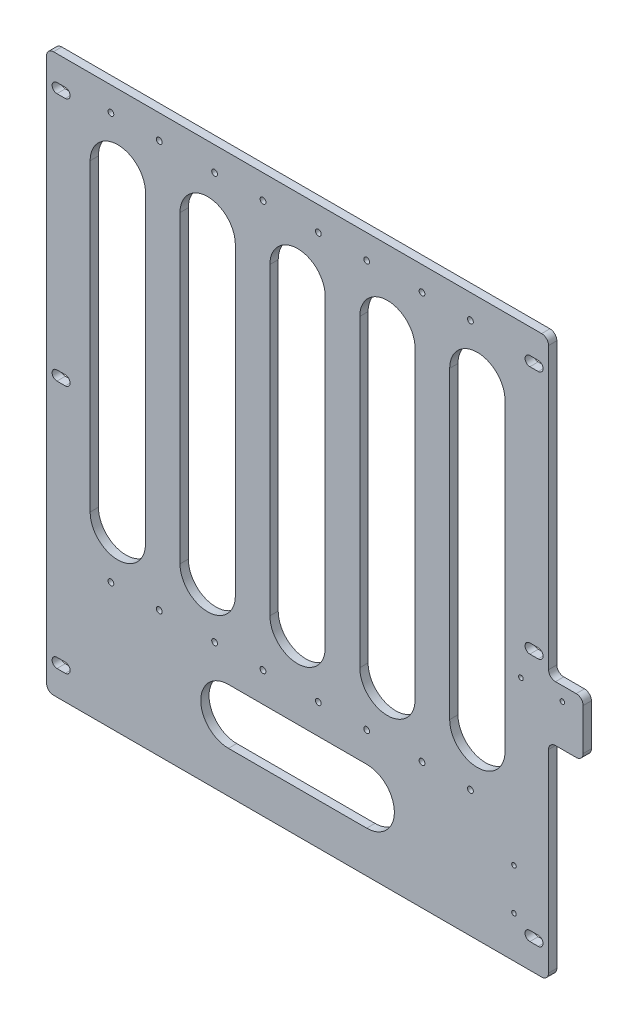
SolidWorks part; units mm, degrees
material "A-玻璃纤维"
ref_plane "前视基准面" through (0, 0, 0) normal (0, 0, 1) x (1, 0, 0)
ref_plane "上视基准面" through (0, 0, 0) normal (0, 1, 0) x (1, 0, 0)
ref_plane "右视基准面" through (0, 0, 0) normal (1, 0, 0) x (0, 0, -1)
sketch "草图1" plane through (0, 0, 0) normal (0, 0, 1) x (1, 0, 0)
  line L1 (-181.5, 201.5) -> (181.5, 201.5)
  line L2 (-181.5, 201.5) -> (-181.5, -201.5)
  line L3 (-181.5, -201.5) -> (181.5, -201.5)
  line L4 (181.5, 201.5) -> (181.5, -201.5)
  line L5 (-181.5, 201.5) -> (181.5, -201.5) construction
  line L6 (-181.5, -201.5) -> (181.5, 201.5) construction
  point P0 (0, 0)
  dimension "D1" = 363
  dimension "D2" = 403
extrude "凸台-拉伸1" add sketch "草图1" along normal blind 6
fillet "圆角1" radius 5 4 edges at (-181.5, 201.5, 3) (181.5, 201.5, 3) (181.5, -201.5, 3) (-181.5, -201.5, 3)
sketch "草图3" plane through (0, 0, 6) normal (0, 0, 1) x (1, 0, 0)
  line L0 (0, 0) -> (-324.6657, 0) construction
  line L2 (0, 0) -> (0, 277.8571) construction
  line L4 (-181.5, 196.5) -> (-181.5, -196.5) construction
  circle A0 centre (-171, -180) radius 3.5
  circle A1 centre (-171, 180) radius 3.5
  circle A3 centre (-171, 0) radius 3.5
  circle A4 centre (171, 0) radius 3.5
  circle A5 centre (171, 180) radius 3.5
  circle A6 centre (171, -180) radius 3.5
  point P0 (-171, -180)
  dimension "D4" = 7
  dimension "D3" = 7
  dimension "D6" = 7
  dimension "D1" = 10.5
  dimension "D2" = 180
  dimension "D8" = 180
extrude "切除-拉伸2" cut sketch "草图3" against normal blind 10
hole_wizard "M5 螺纹孔1" positions "草图4" profile "草图5" tap size "M5" standard "GB"
sketch "草图4" plane through (0, 0, 6) normal (0, 0, 1) x (1, 0, 0)
  line L0 (0, 0) -> (-232.1316, 0) construction
  line L2 (-181.5, 196.5) -> (-181.5, -196.5) construction
  line L4 (0, 0) -> (0, 259.9529) construction
  point P0 (-135, -110)
  point P2 (-100, -110)
  point P40 (-135, 184)
  point P42 (-100, 184)
  point P52 (-60, -110)
  point P53 (-25, -110)
  point P54 (-60, 184)
  point P55 (-25, 184)
  point P56 (15, -110)
  point P57 (50, -110)
  point P58 (15, 184)
  point P59 (50, 184)
  point P60 (90, -110)
  point P61 (125, -110)
  point P62 (90, 184)
  point P63 (125, 184)
  dimension "D1" = 110
  dimension "D2" = 4
  dimension "D3" = 46.5
  dimension "D4" = 35
  dimension "D5" = 46.5
  dimension "D6" = 35
  dimension "D7" = 294
sketch "草图5" plane through (-135, -110, 6) normal (1, 0, 0) x (0, -1, 0)
  line L0 (0, 0) -> (0, 13.6618)
  line L1 (0, 13.6618) -> (2.1, 12.4)
  line L2 (2.1, 12.4) -> (2.1, 0)
  line L5 (2.1, 0) -> (0, 0)
  line L10 (0, 13.6618) -> (-2.1, 12.4) construction
  line L11 (0, -6.35) -> (0, 107.95) construction
  dimension "螺纹孔钻头直径" = 4.2
  dimension "螺纹孔钻头深度" = 12.4
  dimension "导头角度" = 118
cosmetic thread "孔螺蚊线1" parameters "D1"=6, "D2"=5
cosmetic thread "孔螺蚊线2" parameters "D1"=6, "D2"=5
cosmetic thread "孔螺蚊线3" parameters "D1"=6, "D2"=5
cosmetic thread "孔螺蚊线4" parameters "D1"=6, "D2"=5
cosmetic thread "孔螺蚊线5" parameters "D1"=6, "D2"=5
cosmetic thread "孔螺蚊线6" parameters "D1"=6, "D2"=5
cosmetic thread "孔螺蚊线7" parameters "D1"=6, "D2"=5
cosmetic thread "孔螺蚊线8" parameters "D1"=6, "D2"=5
cosmetic thread "孔螺蚊线9" parameters "D1"=6, "D2"=5
cosmetic thread "孔螺蚊线10" parameters "D1"=6, "D2"=5
cosmetic thread "孔螺蚊线11" parameters "D1"=6, "D2"=5
cosmetic thread "孔螺蚊线12" parameters "D1"=6, "D2"=5
cosmetic thread "孔螺蚊线13" parameters "D1"=6, "D2"=5
cosmetic thread "孔螺蚊线14" parameters "D1"=6, "D2"=5
cosmetic thread "孔螺蚊线15" parameters "D1"=6, "D2"=5
cosmetic thread "孔螺蚊线16" parameters "D1"=6, "D2"=5
sketch "草图6" plane through (0, 0, 6) normal (0, 0, 1) x (1, 0, 0)
  line L0 (-174, 180) -> (-168, 180) construction
  line L1 (-174, 183.5) -> (-168, 183.5)
  line L2 (-174, 176.5) -> (-168, 176.5)
  line L3 (168, 180) -> (174, 180) construction
  line L4 (168, 183.5) -> (174, 183.5)
  line L5 (168, 176.5) -> (174, 176.5)
  line L6 (168, 0) -> (174, 0) construction
  line L7 (168, 3.5) -> (174, 3.5)
  line L8 (168, -3.5) -> (174, -3.5)
  line L9 (168, -180) -> (174, -180) construction
  line L10 (168, -176.5) -> (174, -176.5)
  line L11 (168, -183.5) -> (174, -183.5)
  line L12 (-174, 0) -> (-168, 0) construction
  line L13 (-174, 3.5) -> (-168, 3.5)
  line L14 (-174, -3.5) -> (-168, -3.5)
  line L15 (-174, -180) -> (-168, -180) construction
  line L16 (-174, -176.5) -> (-168, -176.5)
  line L17 (-174, -183.5) -> (-168, -183.5)
  arc A0 (-174, 183.5) -> (-174, 176.5) centre (-174, 180) ccw
  arc A1 (-168, 176.5) -> (-168, 183.5) centre (-168, 180) ccw
  arc A2 (168, 183.5) -> (168, 176.5) centre (168, 180) ccw
  arc A3 (174, 176.5) -> (174, 183.5) centre (174, 180) ccw
  arc A4 (168, 3.5) -> (168, -3.5) centre (168, 0) ccw
  arc A5 (174, -3.5) -> (174, 3.5) centre (174, 0) ccw
  arc A6 (168, -176.5) -> (168, -183.5) centre (168, -180) ccw
  arc A7 (174, -183.5) -> (174, -176.5) centre (174, -180) ccw
  arc A8 (-174, 3.5) -> (-174, -3.5) centre (-174, 0) ccw
  arc A9 (-168, -3.5) -> (-168, 3.5) centre (-168, 0) ccw
  arc A10 (-174, -176.5) -> (-174, -183.5) centre (-174, -180) ccw
  arc A11 (-168, -183.5) -> (-168, -176.5) centre (-168, -180) ccw
  point P2 (-171, 180)
  point P13 (171, 180)
  point P20 (171, 0)
  point P27 (171, -180)
  point P34 (-171, 0)
  point P41 (-171, -180)
  dimension "D1" = 3.5
  dimension "D2" = 6
  dimension "D3" = 3
extrude "切除-拉伸3" cut sketch "草图6" against normal blind 10
sketch "草图7" plane through (0, 0, 6) normal (0, 0, 1) x (1, 0, 0)
  line L0 (0, 0) -> (0, -242.9538) construction
  line L1 (-176.5, -201.5) -> (176.5, -201.5) construction
  line L5 (90, -110) -> (125, -110) construction
  line L9 (-50, -151.5) -> (50, -151.5) construction
  line L10 (-50, -131.5) -> (50, -131.5)
  line L11 (-50, -171.5) -> (50, -171.5)
  arc A4 (-50, -131.5) -> (-50, -171.5) centre (-50, -151.5) ccw
  arc A5 (50, -171.5) -> (50, -131.5) centre (50, -151.5) ccw
  point P25 (0, -151.5)
  dimension "D6" = 20
  dimension "D1" = 50
  dimension "D5" = 100
extrude "切除-拉伸4" cut sketch "草图7" against normal blind 10
sketch "草图8" plane through (0, 0, 6) normal (0, 0, 1) x (1, 0, 0)
  line L0 (0, 0) -> (0, 274.3481) construction
  line L1 (0, 0) -> (268.4269, 0) construction
  line L2 (0, 146.5) -> (0, -73.5) construction
  line L3 (20, 146.5) -> (20, -73.5)
  line L4 (-20, 146.5) -> (-20, -73.5)
  line L5 (176.5, 201.5) -> (-176.5, 201.5) construction
  line L6 (65, 146.5) -> (65, -73.5) construction
  line L7 (85, 146.5) -> (85, -73.5)
  line L8 (45, 146.5) -> (45, -73.5)
  line L9 (130, 146.5) -> (130, -73.5) construction
  line L10 (150, 146.5) -> (150, -73.5)
  line L11 (110, 146.5) -> (110, -73.5)
  line L12 (-130, 146.5) -> (-130, -73.5) construction
  line L13 (-150, 146.5) -> (-150, -73.5)
  line L14 (-110, 146.5) -> (-110, -73.5)
  line L15 (-65, 146.5) -> (-65, -73.5) construction
  line L16 (-85, 146.5) -> (-85, -73.5)
  line L17 (-45, 146.5) -> (-45, -73.5)
  line L18 (0, 0) -> (0, -232.9351) construction
  arc A0 (20, 146.5) -> (-20, 146.5) centre (0, 146.5) ccw
  arc A1 (-20, -73.5) -> (20, -73.5) centre (0, -73.5) ccw
  arc A2 (85, 146.5) -> (45, 146.5) centre (65, 146.5) ccw
  arc A3 (45, -73.5) -> (85, -73.5) centre (65, -73.5) ccw
  arc A4 (150, 146.5) -> (110, 146.5) centre (130, 146.5) ccw
  arc A5 (110, -73.5) -> (150, -73.5) centre (130, -73.5) ccw
  arc A6 (-150, 146.5) -> (-110, 146.5) centre (-130, 146.5) cw
  arc A7 (-110, -73.5) -> (-150, -73.5) centre (-130, -73.5) cw
  arc A8 (-85, 146.5) -> (-45, 146.5) centre (-65, 146.5) cw
  arc A9 (-45, -73.5) -> (-85, -73.5) centre (-65, -73.5) cw
  point P6 (0, 36.5)
  point P16 (65, 36.5)
  point P23 (130, 36.5)
  point P29 (-130, 36.5)
  point P36 (-65, 36.5)
  dimension "D3" = 20
  dimension "D1" = 55
  dimension "D2" = 220
  dimension "D4" = 3
extrude "切除-拉伸5" cut sketch "草图8" against normal blind 10
hole_wizard "M4 螺纹孔1" positions "草图9" profile "草图10" tap size "M4" standard "GB"
sketch "草图9" plane through (0, 0, 6) normal (0, 0, 1) x (1, 0, 0)
  line L0 (-176.5, -201.5) -> (176.5, -201.5) construction
  line L2 (181.5, -196.5) -> (181.5, 196.5) construction
  point P0 (156.5, -171.5)
  point P2 (156.5, -141.5)
  dimension "D1" = 30
  dimension "D2" = 25
  dimension "D3" = 30
sketch "草图10" plane through (156.5, -171.5, 6) normal (1, 0, 0) x (0, -1, 0)
  line L0 (0, 0) -> (0, 11.0914)
  line L1 (0, 11.0914) -> (1.65, 10.1)
  line L2 (1.65, 10.1) -> (1.65, 0)
  line L5 (1.65, 0) -> (0, 0)
  line L10 (0, 11.0914) -> (-1.65, 10.1) construction
  line L11 (0, -6.35) -> (0, 107.95) construction
  dimension "螺纹孔钻头直径" = 3.3
  dimension "螺纹孔钻头深度" = 10.1
  dimension "导头角度" = 118
cosmetic thread "孔螺蚊线17" parameters "D1"=6, "D2"=4
cosmetic thread "孔螺蚊线18" parameters "D1"=6, "D2"=4
sketch "草图11" plane through (0, 0, 6) normal (0, 0, 1) x (1, 0, 0)
  line L0 (181.5, -196.5) -> (181.5, 196.5) construction
  line L1 (181.5, -11.5) -> (206.5, -11.5)
  line L2 (181.5, -11.5) -> (181.5, -51.5)
  line L3 (181.5, -51.5) -> (206.5, -51.5)
  line L4 (206.5, -11.5) -> (206.5, -51.5)
  line L5 (-176.5, -201.5) -> (176.5, -201.5) construction
  dimension "D1" = 150
  dimension "D2" = 40
  dimension "D3" = 25
extrude "凸台-拉伸2" add sketch "草图11" against normal up to surface (6 mm away) up to face at (158.15, -171.5, 0)
hole_wizard "M4 螺纹孔2" positions "草图12" profile "草图13" tap size "M4" standard "GB"
sketch "草图12" plane through (0, 0, 6) normal (0, 0, 1) x (1, 0, 0)
  line L0 (-176.5, -201.5) -> (176.5, -201.5) construction
  line L1 (181.5, -11.5) -> (181.5, 196.5) construction
  point P0 (161.5, -21.5)
  point P2 (191.5, -21.5)
  dimension "D1" = 180
  dimension "D2" = 20
  dimension "D3" = 30
  dimension "D4" = 180
sketch "草图13" plane through (161.5, -21.5, 6) normal (1, 0, 0) x (0, -1, 0)
  line L0 (0, 0) -> (0, 11.0914)
  line L1 (0, 11.0914) -> (1.65, 10.1)
  line L2 (1.65, 10.1) -> (1.65, 0)
  line L5 (1.65, 0) -> (0, 0)
  line L10 (0, 11.0914) -> (-1.65, 10.1) construction
  line L11 (0, -6.35) -> (0, 107.95) construction
  dimension "螺纹孔钻头直径" = 3.3
  dimension "螺纹孔钻头深度" = 10.1
  dimension "导头角度" = 118
cosmetic thread "孔螺蚊线19" parameters "D1"=6, "D2"=4
cosmetic thread "孔螺蚊线20" parameters "D1"=6, "D2"=4
fillet "圆角2" radius 5 4 edges at (181.5, -11.5, 3) (206.5, -11.5, 3) (181.5, -51.5, 3) (206.5, -51.5, 3)
sketch "折弯-线1" plane through (0, 0, 0) normal (0, 1, 0) x (1, 0, 0)
sketch "边界框1" plane through (0, 0, 0) normal (0, 1, 0) x (1, 0, 0)
